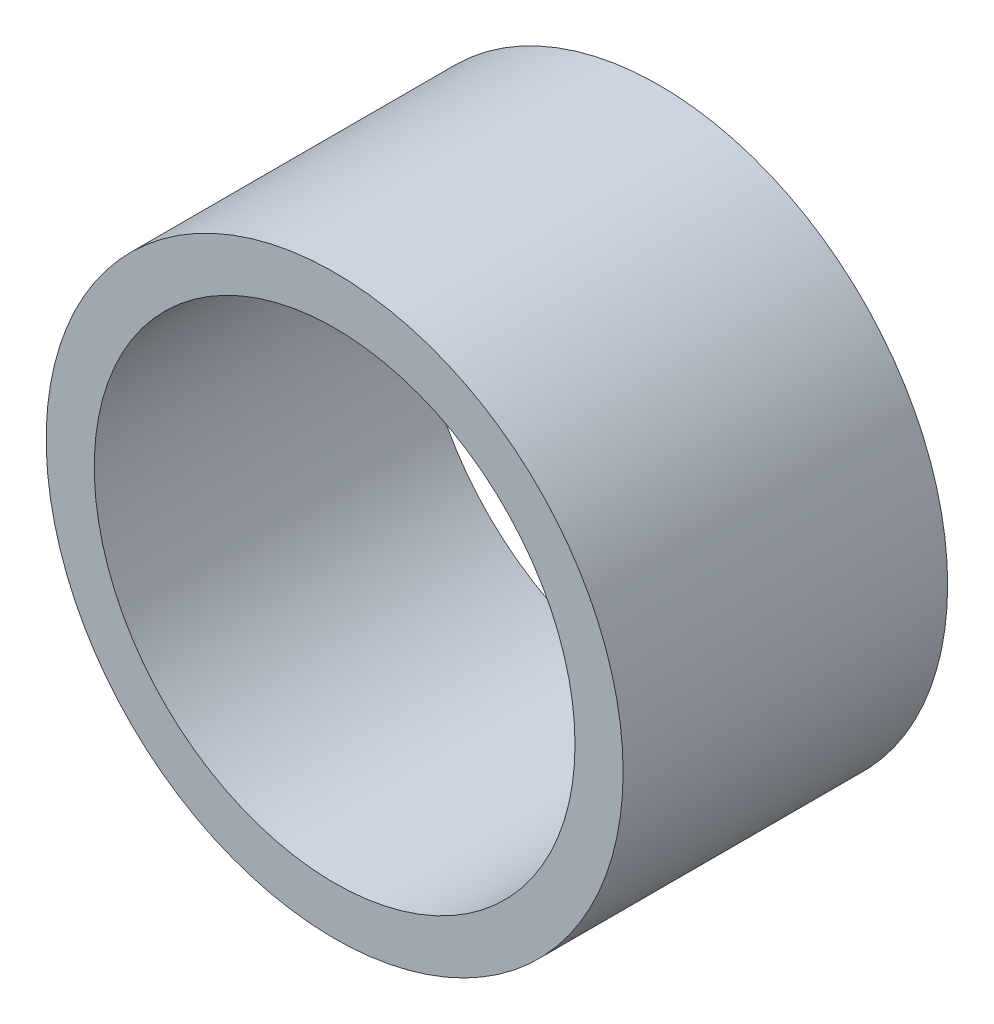
SolidWorks part; units mm, degrees
material "6061 合金"
ref_plane "前视基准面" through (0, 0, 0) normal (0, 0, 1) x (1, 0, 0)
ref_plane "上视基准面" through (0, 0, 0) normal (0, 1, 0) x (1, 0, 0)
ref_plane "右视基准面" through (0, 0, 0) normal (1, 0, 0) x (0, 0, -1)
other "Configuration Table"
sketch "草图1" plane through (0, 0, 0) normal (0, 0, 1) x (1, 0, 0)
  circle A0 centre (0, 0) radius 5
  circle A1 centre (0, 0) radius 6
  dimension "D1" = 10
  dimension "D2" = 12
extrude "凸台-拉伸1" add sketch "草图1" along normal blind 6.75 contours A0 | A1
sketch "草图2" plane through (0, 0, 0) normal (0, 0, -1) x (-1, 0, 0)
  circle A0 centre (0, 0) radius 6
  circle A1 centre (0, 0) radius 5 construction
  circle A2 centre (0, 0) radius 5
  dimension "D1" = 12
extrude "凸台-拉伸2" [suppressed] add sketch "草图2" against normal blind 1
sketch "草图3" [suppressed] plane through (0, 0, 15) normal (0, 0, 1) x (1, 0, 0)
  circle A1 centre (0, 0) radius 5 construction
  circle A2 centre (0, 0) radius 5
  circle A3 centre (0, 0) radius 7 construction
  circle A4 centre (0, 0) radius 7
extrude "凸台-拉伸3" [suppressed] add sketch "草图3" against normal blind 1
fillet "圆角1" [suppressed] radius 0.5
chamfer "倒角1" [suppressed] distance 0.5 angle 45
